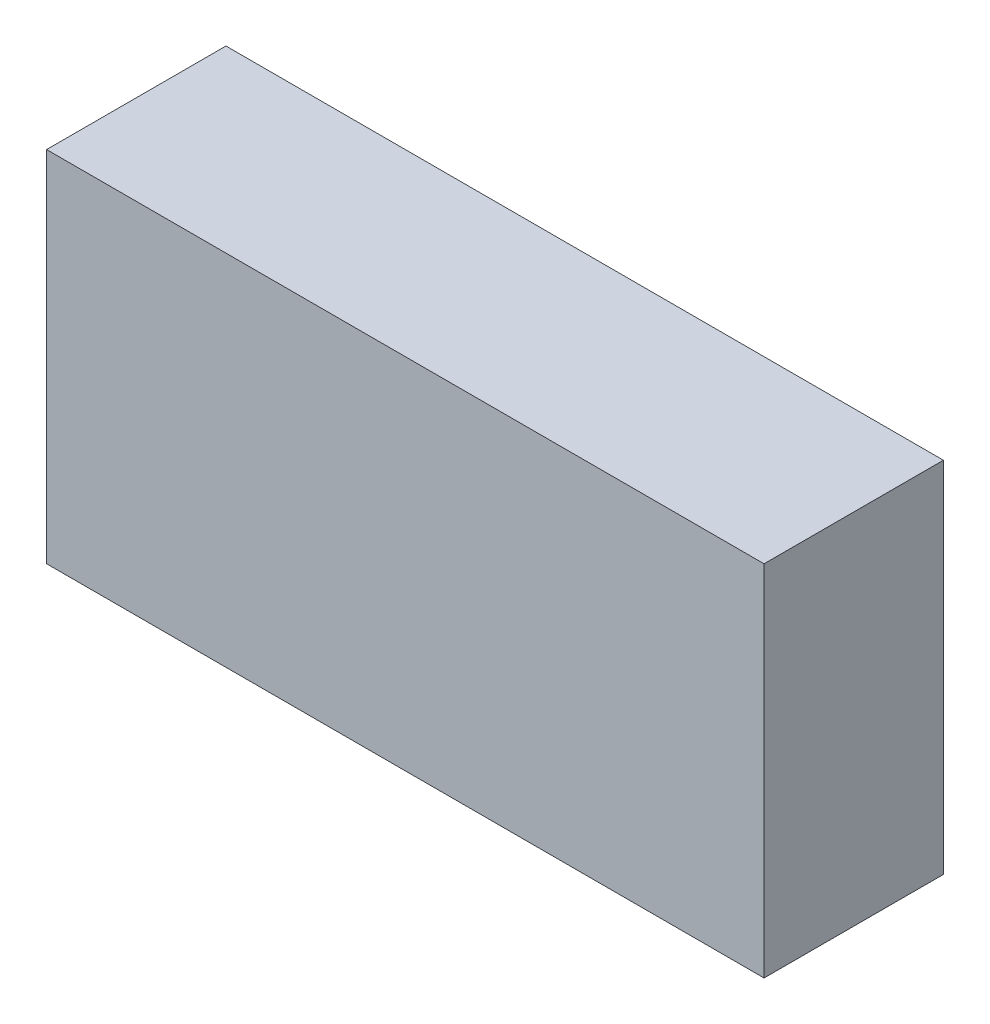
SolidWorks part; units mm, degrees
ref_plane "Front Plane" through (0, 0, 0) normal (0, 0, 1) x (1, 0, 0)
ref_plane "Top Plane" through (0, 0, 0) normal (0, 1, 0) x (1, 0, 0)
ref_plane "Right Plane" through (0, 0, 0) normal (1, 0, 0) x (0, 0, -1)
sketch "Sketch1" plane through (0, 0, 0) normal (0, 0, 1) x (1, 0, 0)
  line L1 (0, 0) -> (140, 0)
  line L2 (0, 0) -> (0, 70)
  line L3 (0, 70) -> (140, 70)
  line L4 (140, 0) -> (140, 70)
  dimension "D1" = 140
  dimension "D2" = 70
extrude "Boss-Extrude1" add sketch "Sketch1" along normal blind 35
